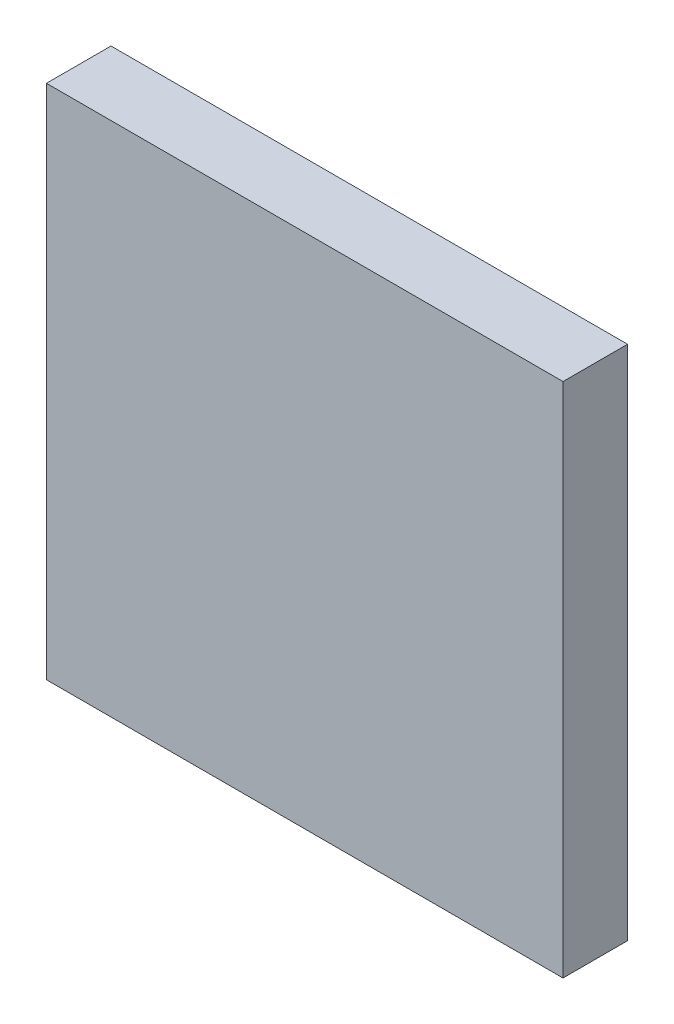
SolidWorks part; units mm, degrees
ref_plane "Front Plane" through (0, 0, 0) normal (0, 0, 1) x (1, 0, 0)
ref_plane "Top Plane" through (0, 0, 0) normal (0, 1, 0) x (1, 0, 0)
ref_plane "Right Plane" through (0, 0, 0) normal (1, 0, 0) x (0, 0, -1)
sketch "Sketch1" plane through (0, 0, 0) normal (0, 0, 1) x (1, 0, 0)
  line L1 (0, 0) -> (8, 0)
  line L2 (0, 0) -> (0, 8)
  line L3 (0, 8) -> (8, 8)
  line L4 (8, 0) -> (8, 8)
  dimension "D1" = 8
extrude "Profile" add sketch "Sketch1" along normal blind 1
equation "\"Profile_Depth\"= 1mm"
equation "\"D1@Profile\" = \"Profile_Depth\""
equation "\"Profile_Sketch_1\"= 8mm"
equation "\"D1@Sketch1\" = \"Profile_Sketch_1\""
equation "\"EnvelopeWidth\"= 8mm"
equation "\"EnvelopeHeight\"= 8mm"
